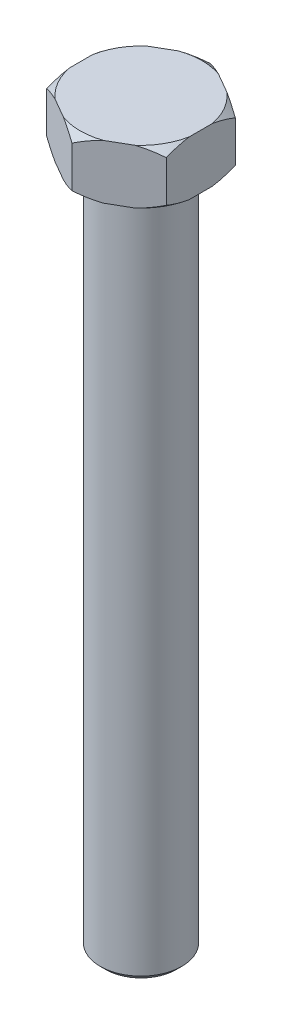
SolidWorks part; units mm, degrees
ref_plane "Front Plane" through (0, 0, 0) normal (0, 0, 1) x (1, 0, 0)
ref_plane "Top Plane" through (0, 0, 0) normal (0, 1, 0) x (1, 0, 0)
ref_plane "Right Plane" through (0, 0, 0) normal (1, 0, 0) x (0, 0, -1)
sketch "Sketch1" plane through (0, 0, 0) normal (0, 1, 0) x (1, 0, 0)
  line L1 (11, -6.3509) -> (11, 6.3509)
  line L2 (11, 6.3509) -> (0, 12.7017)
  line L3 (0, 12.7017) -> (-11, 6.3509)
  line L4 (-11, 6.3509) -> (-11, -6.3509)
  line L5 (-11, -6.3509) -> (0, -12.7017)
  line L6 (0, -12.7017) -> (11, -6.3509)
  circle A0 centre (0, 0) radius 11 construction
  dimension "D1" = 22
extrude "Boss-Extrude1" add sketch "Sketch1" against normal blind 10
sketch "Sketch2" plane through (0, -10, 0) normal (0, -1, 0) x (1, 0, 0)
  circle A0 centre (0, 0) radius 7.5
  dimension "D1" = 15
extrude "Boss-Extrude2" add sketch "Sketch2" along normal blind 126
cosmetic thread "Cosmetic Thread1"
sketch "Sketch3" plane through (0, 0, 0) normal (1, 0, 0) x (0, 0, -1)
  line L0 (0, 3.8663) -> (0, -12.2264) construction
  line L1 (-12.7017, 0) -> (-12.7017, -1.2)
  line L2 (-12.7017, -10) -> (-12.7017, 0) construction
  line L3 (-12.7017, -1.2) -> (-11.2017, 0)
  line L4 (-12.7017, 0) -> (-6.3509, 0) construction
  line L5 (-11.2017, 0) -> (-12.7017, 0)
  line L6 (-15.672, -5) -> (-8.3237, -5) construction
  line L7 (-11.2017, -10) -> (-12.7017, -10)
  line L9 (-12.7017, -8.8) -> (-11.2017, -10)
  line L10 (-12.7017, -7.5235) -> (-12.7327, -7.5235)
  line L11 (-12.7017, -10) -> (-12.7017, -8.8)
  dimension "D1" = 1.5
  dimension "D2" = 1.2
revolve "Cut-Revolve1" cut sketch "Sketch3" angle 360 about L0
chamfer "Chamfer1" distance 1 angle 45 1 edges at (0, -136, -7.5)
scale "Scale1" scale about centroid uniform scaling yes scale factor 0.25
